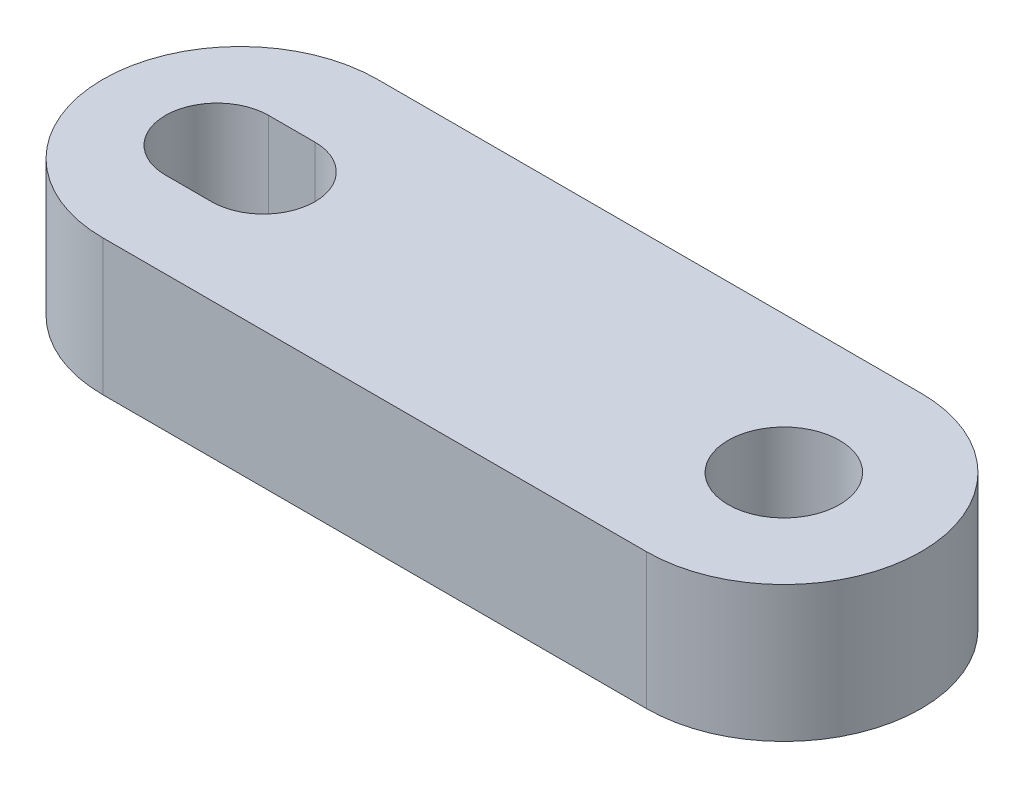
SolidWorks part; units mm, degrees
ref_plane "前基準面" through (0, 0, 0) normal (0, 0, 1) x (1, 0, 0)
ref_plane "上基準面" through (0, 0, 0) normal (0, 1, 0) x (1, 0, 0)
ref_plane "右基準面" through (0, 0, 0) normal (1, 0, 0) x (0, 0, -1)
sketch "草圖1" plane through (0, 0, 0) normal (0, 1, 0) x (1, 0, 0)
  line L0 (-35.9568, 0) -> (39.8148, 0) construction
  line L1 (-10, 0) -> (10, 0) construction
  line L2 (-10, 5.05) -> (10, 5.05)
  line L3 (-10, -5.05) -> (10, -5.05)
  line L4 (-10.85, 0) -> (-9.15, 0) construction
  line L5 (-10.85, 1.9) -> (-9.15, 1.9)
  line L6 (-10.85, -1.9) -> (-9.15, -1.9)
  arc A0 (-10, 5.05) -> (-10, -5.05) centre (-10, 0) ccw
  arc A1 (10, -5.05) -> (10, 5.05) centre (10, 0) ccw
  circle A3 centre (10, 0) radius 2.05
  arc A4 (-10.85, 1.9) -> (-10.85, -1.9) centre (-10.85, 0) ccw
  arc A5 (-9.15, -1.9) -> (-9.15, 1.9) centre (-9.15, 0) ccw
  point P5 (0, 0)
  point P14 (-10, 0)
  point P21 (-12.75, 0)
  point P22 (-7.25, 0)
  dimension "D2" = 3
  dimension "D3" = 4.1
  dimension "D5" = 3.8
  dimension "D1" = 20
  dimension "D4" = 5.5
extrude "填料-伸長1" add sketch "草圖1" along normal blind 5
sketch "草圖2" plane through (0, 5, 0) normal (0, 1, 0) x (1, 0, 0)
  circle A0 centre (-10, 0) radius 5
